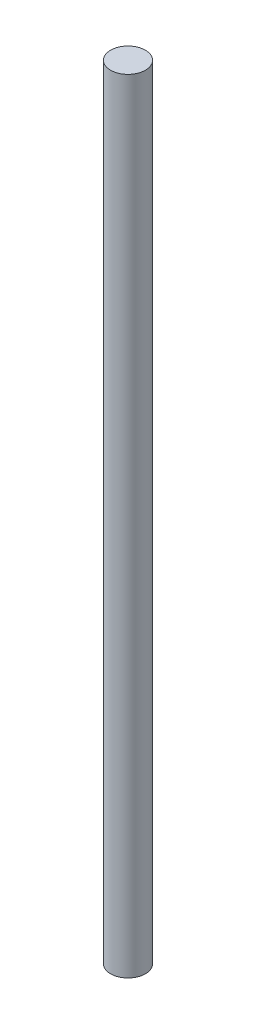
SolidWorks part; units mm, degrees
ref_plane "Front Plane" through (0, 0, 0) normal (0, 0, 1) x (1, 0, 0)
ref_plane "Top Plane" through (0, 0, 0) normal (0, 1, 0) x (1, 0, 0)
ref_plane "Right Plane" through (0, 0, 0) normal (1, 0, 0) x (0, 0, -1)
sketch "Sketch1" plane through (0, 0, 0) normal (0, 1, 0) x (1, 0, 0)
  circle A0 centre (0, 0) radius 2.032
  dimension "D1" = 4.064
extrude "Boss-Extrude1" add sketch "Sketch1" along normal blind 91.44
equation "\"3.7o\"=3.75"
